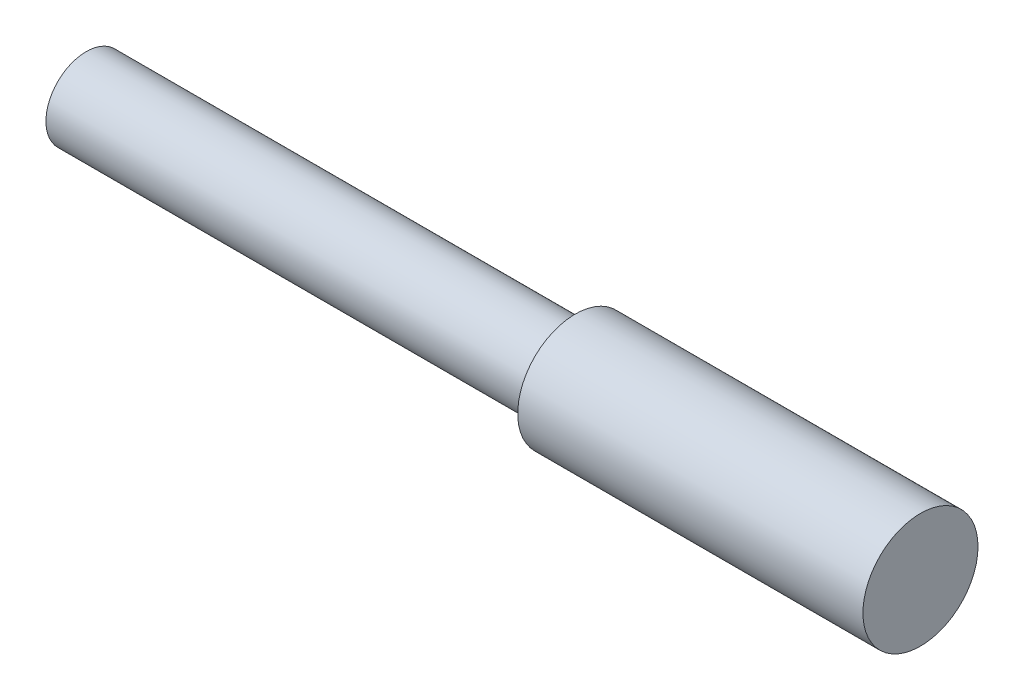
SolidWorks part; units mm, degrees
material "1023 Carbon Steel Sheet (SS)"
ref_plane "Front Plane" through (0, 0, 0) normal (0, 0, 1) x (1, 0, 0)
ref_plane "Top Plane" through (0, 0, 0) normal (0, 1, 0) x (1, 0, 0)
ref_plane "Right Plane" through (0, 0, 0) normal (1, 0, 0) x (0, 0, -1)
sketch "Sketch1" plane through (0, 0, 0) normal (1, 0, 0) x (0, 0, -1)
  circle A0 centre (0, 0) radius 10
  dimension "D1" = 20
extrude "Boss-Extrude1" add sketch "Sketch1" against normal blind 145
ref_plane "Plane1" through (-60, 0, 0) normal (1, 0, 0) x (0, 0, -1)
sketch "Sketch2" plane through (-60, 0, 0) normal (1, 0, 0) x (0, 0, -1)
  circle A0 centre (0, 0) radius 10
  circle A1 centre (0, 0) radius 7
  dimension "D1" = 14
extrude "Cut-Extrude1" cut sketch "Sketch2" against normal blind 97
